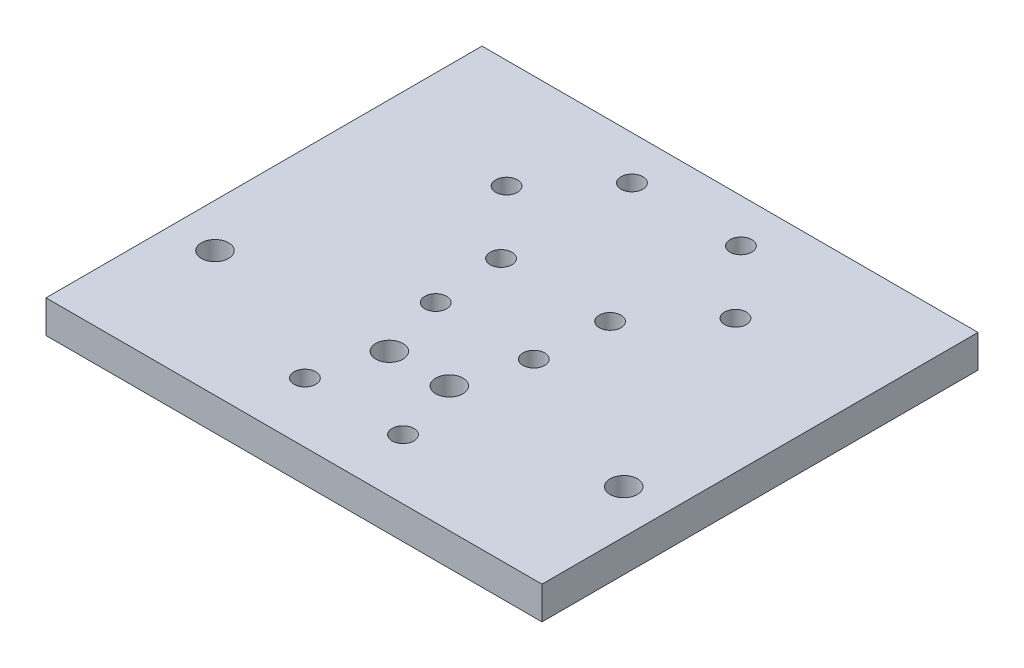
SolidWorks part; units mm, degrees
ref_plane "前视基准面" through (0, 0, 0) normal (0, 0, 1) x (1, 0, 0)
ref_plane "上视基准面" through (0, 0, 0) normal (0, 1, 0) x (1, 0, 0)
ref_plane "右视基准面" through (0, 0, 0) normal (1, 0, 0) x (0, 0, -1)
sketch "草图1" plane through (0, 0, 0) normal (1, 0, 0) x (0, 0, -1)
  line L0 (6, 6) -> (0, 6) construction
  line L1 (0, 0) -> (80, 0)
  line L2 (0, 0) -> (0, 6)
  line L3 (6, 6) -> (80, 6)
  line L4 (80, 0) -> (80, 6)
  line L9 (6, 6) -> (0, 6) construction
  line L10 (0, 6) -> (6, 6)
  dimension "D1" = 6
  dimension "D2" = 80
extrude "凸台-拉伸1" add sketch "草图1" along normal blind 104
sketch "草图2" plane through (0, 6, 0) normal (0, 1, 0) x (1, 0, 0)
  line L0 (97.5, 80) -> (97.5, 0)
  line L1 (52, 7.8345) -> (52, 80) construction
  line L2 (104, 80) -> (0, 80) construction
  line L3 (61, 11) -> (61, 35) construction
  line L4 (104, 23) -> (0, 23) construction
  line L5 (104, 80) -> (104, 0) construction
  line L6 (0, 80) -> (0, 0) construction
  line L15 (52, 7.8345) -> (52, 0) construction
  line L16 (104, 0) -> (0, 0) construction
  line L17 (62, 72) -> (62, 48) construction
  line L18 (68.44, 60) -> (34.9151, 60) construction
  line L19 (97.5, 0) -> (104, 0)
  line L20 (104, 0) -> (104, 80)
  line L21 (104, 80) -> (97.5, 80)
  line L22 (0, 0) -> (0, 80)
  line L23 (6.5, 0) -> (0, 0)
  line L24 (6.5, 80) -> (6.5, 0)
  line L25 (0, 80) -> (6.5, 80)
  circle A0 centre (43, 11) radius 2
  circle A1 centre (43, 35) radius 2
  circle A2 centre (42, 48) radius 2
  circle A3 centre (42, 72) radius 2
  circle A4 centre (62, 72) radius 2
  circle A5 centre (62, 48) radius 2
  circle A6 centre (61, 35) radius 2
  circle A7 centre (61, 11) radius 2
  circle A8 centre (57.5, 23) radius 2.5
  circle A9 centre (89.5, 23) radius 2.5
  circle A10 centre (46.5, 23) radius 2.5
  circle A11 centre (14.5, 23) radius 2.5
  circle A12 centre (73, 60) radius 2
  circle A13 centre (31, 60) radius 2
  point P42 (0, 0)
  point P51 (73, 60)
  point P52 (31, 60)
  dimension "D1" = 24
  dimension "D4" = 24
  dimension "D8" = 32
  dimension "D7" = 5.5
  dimension "D11" = 8
  dimension "D2" = 11
  dimension "D3" = 9
  dimension "D5" = 10
  dimension "D6" = 8
  dimension "D9" = 21
  dimension "D10" = 42
extrude "切除-拉伸1" cut sketch "草图2" against normal through all
